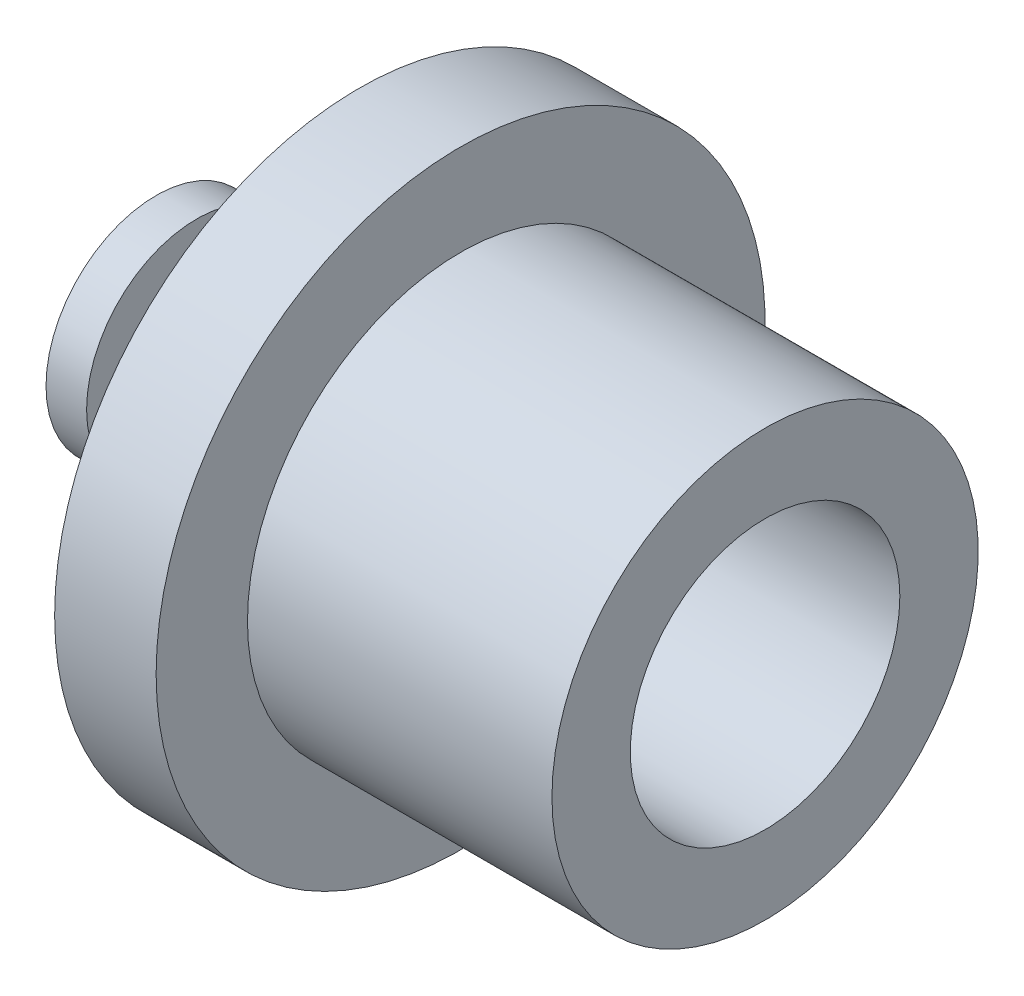
SolidWorks part; units mm, degrees
material "6061-T6 (SS)"
ref_plane "Front Plane" through (0, 0, 0) normal (0, 0, 1) x (1, 0, 0)
ref_plane "Top Plane" through (0, 0, 0) normal (0, 1, 0) x (1, 0, 0)
ref_plane "Right Plane" through (0, 0, 0) normal (1, 0, 0) x (0, 0, -1)
sketch "Sketch1" plane through (0, 0, 0) normal (0, 0, 1) x (1, 0, 0)
  line L0 (0, 0) -> (17.3276, 0) construction
  line L1 (6.35, 3.4449) -> (6.35, 9.525)
  line L2 (6.35, 9.525) -> (9.525, 9.525)
  line L3 (9.525, 9.525) -> (9.525, 6.6675)
  line L4 (9.525, 6.6675) -> (19.05, 6.6675)
  line L5 (19.05, 6.6675) -> (19.05, 0)
  line L6 (19.05, 0) -> (0, 0)
  line L7 (0, 0) -> (0, 3.4449)
  line L8 (0, 3.4449) -> (1.27, 3.4449)
  line L9 (3.81, 3.4449) -> (6.35, 3.4449)
  line L11 (1.27, 3.4449) -> (1.27, 2.0733)
  line L12 (1.27, 2.0733) -> (3.81, 2.0733)
  line L13 (3.81, 3.4449) -> (3.81, 2.0733)
  dimension "D1" = 19.05
  dimension "D2" = 13.335
  dimension "D3" = 3.175
  dimension "D4" = 9.525
  dimension "D5" = 6.8897
  dimension "D6" = 1.3716
  dimension "D7" = 2.54
  dimension "D8" = 1.27
  dimension "D9" = 2.54
revolve "Revolve1" add sketch "Sketch1" angle 360 about L0
hole_wizard "Pipe Tap Drill for 1/8 Tap1" positions "Sketch2" profile "Sketch3" hole size "1/8" standard "ANSI Inch"
sketch "Sketch2" plane through (19.05, 0, 0) normal (1, 0, 0) x (0, 0, -1)
  point P0 (0, 0)
sketch "Sketch3" plane through (19.05, 0, 0) normal (0, 1, 0) x (0, 0, -1)
  line L0 (0, 0) -> (0, 12.0585)
  line L1 (0, 12.0585) -> (4.2164, 9.525)
  line L2 (4.2164, 9.525) -> (4.2164, 0)
  line L5 (4.2164, 0) -> (0, 0)
  line L10 (0, 12.0585) -> (-4.2164, 9.525) construction
  line L11 (0, -6.35) -> (0, 107.95) construction
  dimension "Hole Dia." = 8.4328
  dimension "Hole Depth" = 9.525
  dimension "Drill Angle" = 118
hole_wizard "3/32 (0.09375) Diameter Hole2" positions "Sketch4" profile "Sketch5" hole size "3/32" standard "ANSI Inch" end condition through all
sketch "Sketch4" plane through (0, 0, 0) normal (-1, 0, 0) x (0, 0, 1)
  point P0 (0, 0)
sketch "Sketch5" plane through (0, 0, 0) normal (0, 1, 0) x (0, 0, 1)
  line L0 (0, 0) -> (0, 19.05)
  line L1 (0, 19.05) -> (1.1906, 19.05)
  line L2 (1.1906, 19.05) -> (1.1906, 0)
  line L5 (1.1906, 0) -> (0, 0)
  line L11 (0, -6.35) -> (0, 107.95) construction
  dimension "Thru Hole Dia." = 2.3812
  dimension "Thru Hole Depth" = 19.05
